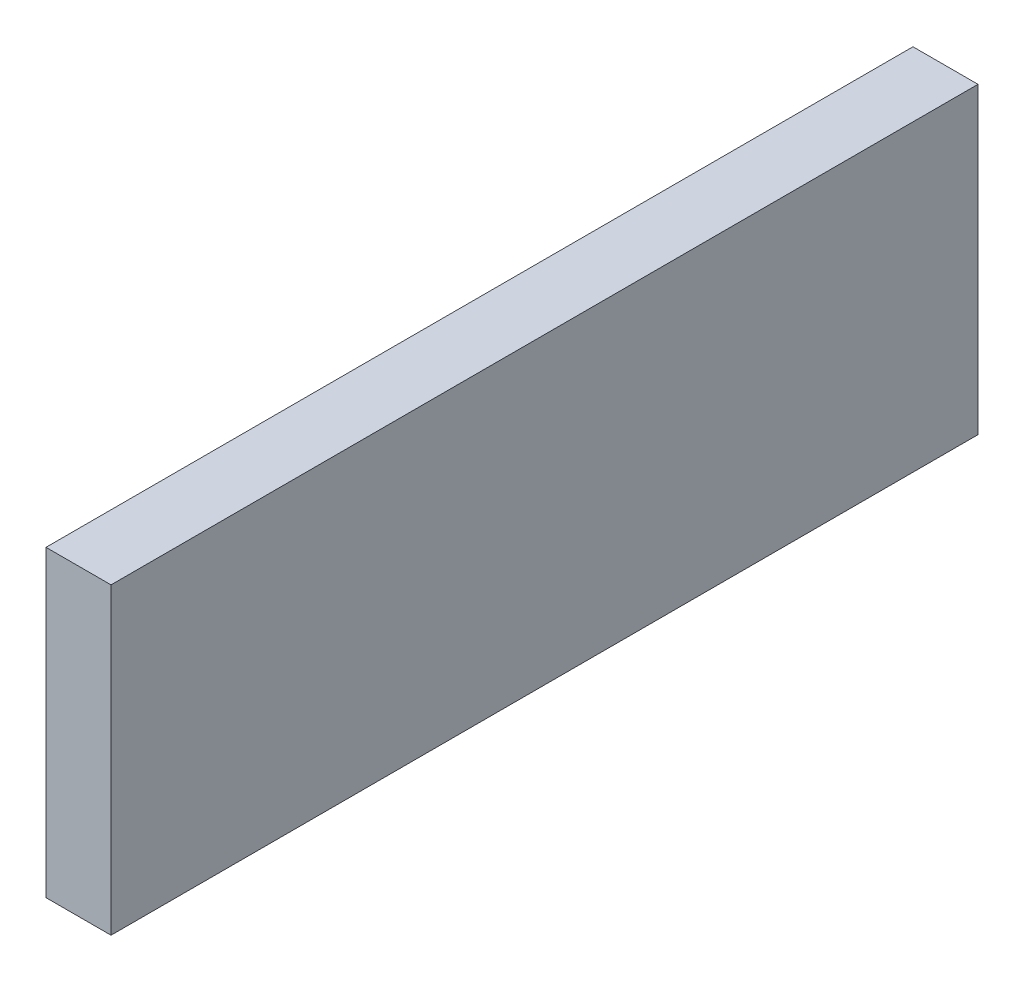
SolidWorks part; units mm, degrees
material "PTFE (general)"
ref_plane "Front Plane" through (0, 0, 0) normal (0, 0, 1) x (1, 0, 0)
ref_plane "Top Plane" through (0, 0, 0) normal (0, 1, 0) x (1, 0, 0)
ref_plane "Right Plane" through (0, 0, 0) normal (1, 0, 0) x (0, 0, -1)
sketch "Sketch1" plane through (0, 0, 0) normal (1, 0, 0) x (0, 0, -1)
  line L1 (-20, -7) -> (20, -7)
  line L2 (-20, -7) -> (-20, 7)
  line L3 (-20, 7) -> (20, 7)
  line L4 (20, -7) -> (20, 7)
  line L5 (-20, -7) -> (20, 7) construction
  line L6 (-20, 7) -> (20, -7) construction
  point P0 (0, 0)
  dimension "D1" = 40
  dimension "D2" = 14
extrude "Boss-Extrude1" add sketch "Sketch1" along normal blind 3
